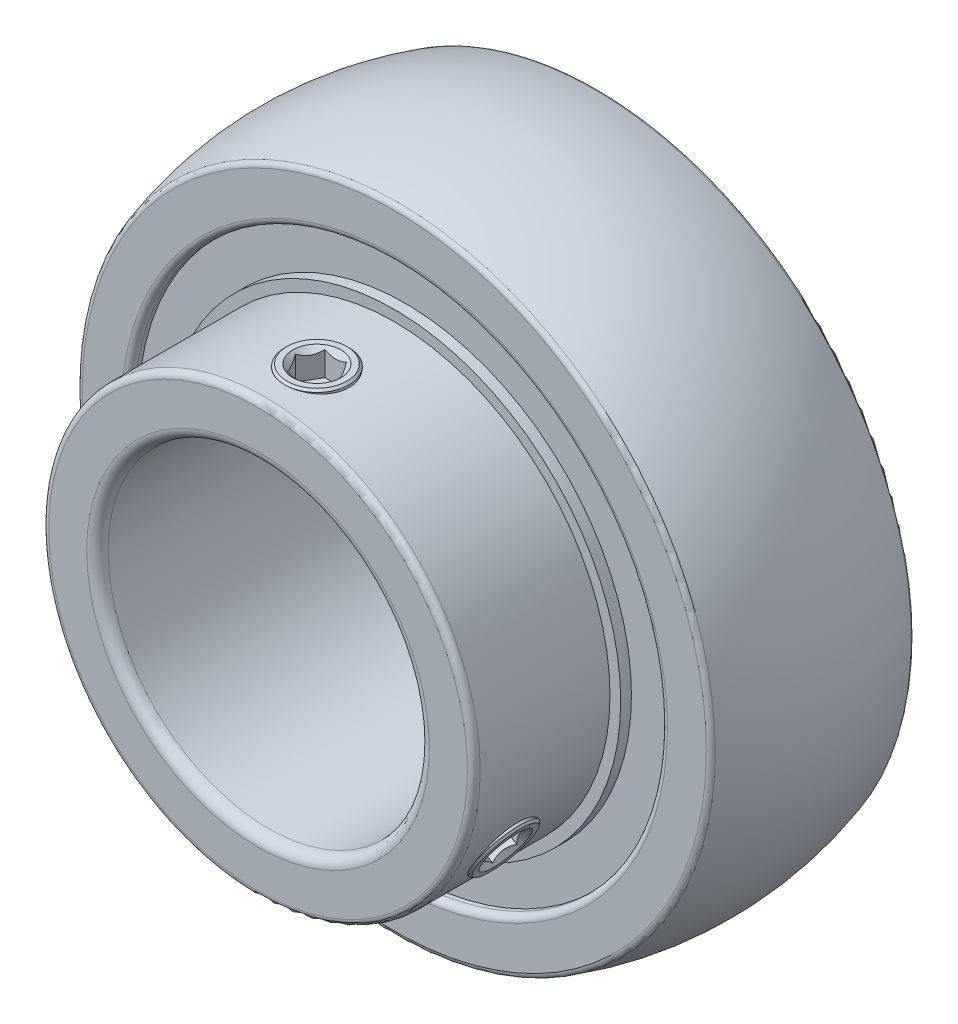
SolidWorks part; units mm, degrees
material "AISI 52100 (100Cr6)"
ref_plane "Plano frontal" through (0, 0, 0) normal (0, 0, 1) x (1, 0, 0)
ref_plane "Plano superior" through (0, 0, 0) normal (0, 1, 0) x (1, 0, 0)
ref_plane "Plano direito" through (0, 0, 0) normal (1, 0, 0) x (0, 0, -1)
sketch "Esboço1" plane through (0, 0, 0) normal (1, 0, 0) x (0, 0, -1)
  line L0 (-996.83, 0) -> (49003.17, 0) construction
  line L1 (-9.5, 29.1419) -> (-9.5, 25.51)
  line L2 (9.5, 20.15) -> (9.5, 21.15)
  line L3 (9.5, 21.15) -> (8.5, 21.15)
  line L4 (8.5, 21.15) -> (8.5, 24.91)
  line L5 (-22.22, 19.55) -> (-22.22, 16)
  line L6 (-21.22, 15) -> (14.88, 15)
  line L7 (15.88, 16) -> (15.88, 19.55)
  line L8 (15.28, 20.15) -> (9.5, 20.15)
  line L9 (-8.9, 24.91) -> (-8.5, 24.91)
  line L10 (8, 24.91) -> (8, 20.15)
  line L11 (-8, 24.91) -> (-8, 20.15)
  line L12 (9.5, 25.51) -> (9.5, 29.1419)
  line L13 (0, 0) -> (0, 31) construction
  line L14 (-8.5, 21.15) -> (-8.5, 24.91)
  line L15 (-9.5, 21.15) -> (-8.5, 21.15)
  line L16 (-9.5, 20.15) -> (-9.5, 21.15)
  line L17 (-8, 24.91) -> (8, 24.91)
  line L18 (-9.5, 20.15) -> (-21.62, 20.15)
  line L19 (8, 20.15) -> (-8, 20.15)
  line L20 (8.5, 24.91) -> (8.9, 24.91)
  arc A0 (-9.1475, 29.6196) -> (9.1475, 29.6196) centre (0, 0) cw
  arc A1 (-9.5, 25.51) -> (-8.9, 24.91) centre (-8.9, 25.51) ccw
  arc A2 (8.9, 24.91) -> (9.5, 25.51) centre (8.9, 25.51) ccw
  arc A3 (15.88, 19.55) -> (15.28, 20.15) centre (15.28, 19.55) ccw
  arc A4 (-21.62, 20.15) -> (-22.22, 19.55) centre (-21.62, 19.55) ccw
  arc A5 (14.88, 15) -> (15.88, 16) centre (14.88, 16) ccw
  arc A6 (-22.22, 16) -> (-21.22, 15) centre (-21.22, 16) ccw
  arc A7 (9.1475, 29.6196) -> (9.5, 29.1419) centre (9, 29.1419) cw
  arc A8 (-9.1475, 29.6196) -> (-9.5, 29.1419) centre (-9, 29.1419) ccw
  dimension "D6" = 0.6
  dimension "D7" = 1
  dimension "D15" = 0.5
  dimension "D11" = 62
  dimension "D2" = 1.5
  dimension "D3" = 19
  dimension "D4" = 38.1
  dimension "D5" = 15.88
  dimension "D8" = 0.5
  dimension "D10" = 30
  dimension "D12" = 49.82
  dimension "D13" = 40.3
revolve "Revolução1" add sketch "Esboço1" angle 360 about L0
sketch "Esboço2" plane through (0, 0, 0) normal (0, 1, 0) x (1, 0, 0)
  line L0 (-19.55, -22.22) -> (19.55, -22.22) construction
  circle A0 centre (0, -16.72) radius 3
  dimension "D1" = 6
  dimension "D2" = 5.5
extrude "Corte-extrusão1" cut sketch "Esboço2" along normal through all
sketch "Esboço3" plane through (0, 0, 0) normal (1, 0, 0) x (0, 0, -1)
  line L0 (-16.72, -1000.5881) -> (-16.72, 48999.4119) construction
  line L1 (-19.52, 20.35) -> (-19.72, 20.15)
  line L2 (-18.97, 20.35) -> (-19.52, 20.35)
  line L3 (-16.72, 17.85) -> (-16.72, 15)
  line L4 (-16.72, 15) -> (-19.12, 15)
  line L5 (-19.72, 20.15) -> (-19.72, 15.6)
  line L6 (-19.72, 15.6) -> (-19.12, 15)
  line L7 (-18.97, 20.35) -> (-18.47, 19.85)
  line L8 (-18.47, 19.85) -> (-18.47, 17.85)
  line L9 (-18.47, 17.85) -> (-16.72, 17.85)
  line L10 (-21.22, 15) -> (14.88, 15) construction
  line L11 (-9.5, 20.15) -> (-21.62, 20.15) construction
  dimension "D1" = 0.2
  dimension "D5" = 2.5
  dimension "D6" = 45
  dimension "D7" = 0.6
  dimension "D8" = 6
  dimension "D9" = 3.5
  dimension "D10" = 4.5
revolve "Revolução2" add sketch "Esboço3" angle 360 about L0
sketch "Esboço4" plane through (0, 20.35, 0) normal (0, 1, 0) x (1, 0, 0)
  line L1 (1.0104, -18.47) -> (2.0207, -16.72)
  line L2 (2.0207, -16.72) -> (1.0104, -14.97)
  line L3 (1.0104, -14.97) -> (-1.0104, -14.97)
  line L4 (-1.0104, -14.97) -> (-2.0207, -16.72)
  line L5 (-2.0207, -16.72) -> (-1.0104, -18.47)
  line L6 (-1.0104, -18.47) -> (1.0104, -18.47)
  circle A0 centre (0, -16.72) radius 1.75 construction
  circle A2 centre (0, -16.72) radius 1.75 construction
extrude "Corte-extrusão2" cut sketch "Esboço4" against normal up to vertex (2.5 mm away) up to point (0, 17.85, 18.47)
pattern_circular "PadrãoCircular1" count 2 over 120 about axis through (0, 0, 0) along (0, 0, 1) of "Revolução2", "Corte-extrusão2", "Corte-extrusão1"
